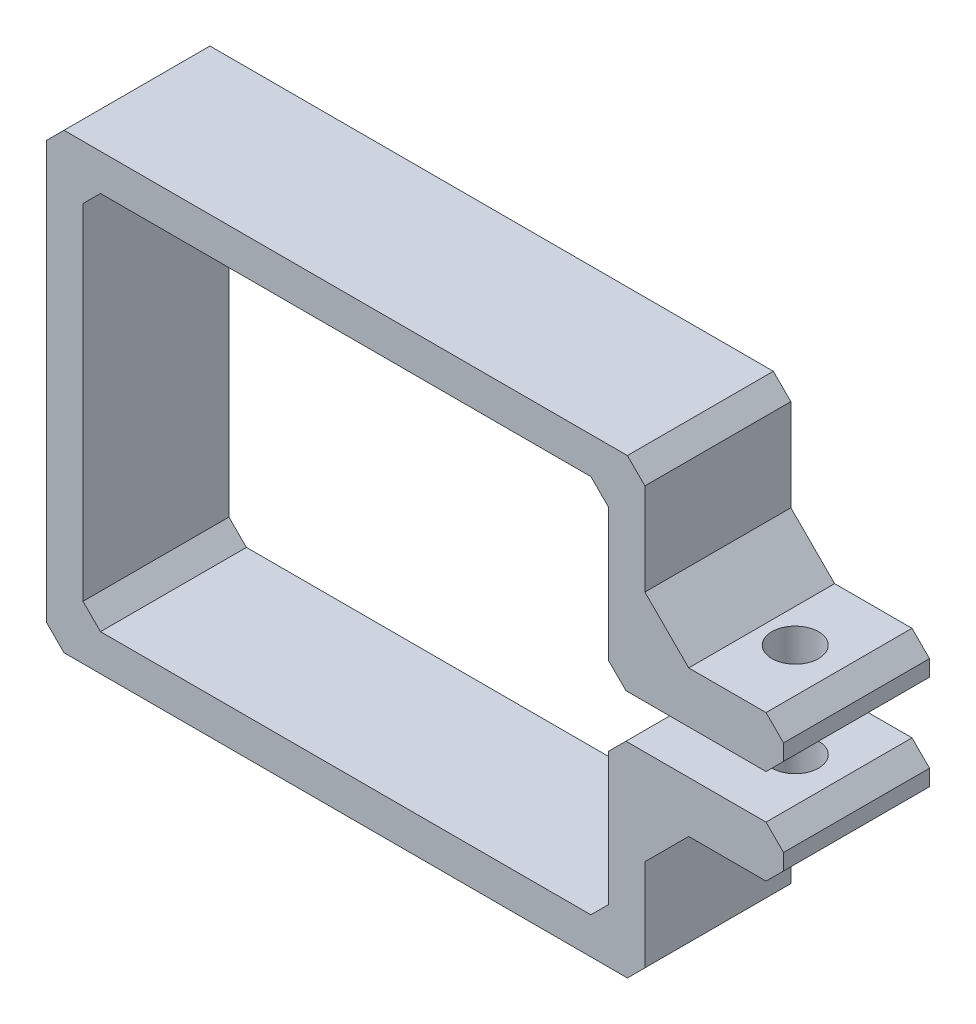
SolidWorks part; units mm, degrees
ref_plane "Front Plane" through (0, 0, 0) normal (0, 0, 1) x (1, 0, 0)
ref_plane "Top Plane" through (0, 0, 0) normal (0, 1, 0) x (1, 0, 0)
ref_plane "Right Plane" through (0, 0, 0) normal (1, 0, 0) x (0, 0, -1)
sketch "Sketch1" plane through (0, 0, 0) normal (0, 0, 1) x (1, 0, 0)
  line L0 (-20.5, 15.5) -> (-20.5, -15.5)
  line L1 (-18, 13) -> (18, 13)
  line L2 (-18, 13) -> (-18, -13)
  line L3 (-18, -13) -> (18, -13)
  line L4 (18, 13) -> (18, -13)
  line L5 (-18, 13) -> (18, -13) construction
  line L6 (-18, -13) -> (18, 13) construction
  line L7 (-20.5, -15.5) -> (20.5, -15.5)
  line L8 (20.5, 15.5) -> (20.5, -15.5)
  line L9 (-20.5, 15.5) -> (20.5, 15.5)
  line L11 (18, 5) -> (30, 5)
  line L12 (18, 5) -> (18, -5)
  line L13 (18, -5) -> (30, -5)
  line L14 (30, 5) -> (30, -5)
  line L15 (18, 5) -> (30, -5) construction
  line L16 (18, -5) -> (30, 5) construction
  line L17 (18, 1.5) -> (30, 1.5)
  line L18 (18, 1.5) -> (18, -1.5)
  line L19 (18, -1.5) -> (30, -1.5)
  line L20 (30, 1.5) -> (30, -1.5)
  line L21 (18, 1.5) -> (30, -1.5) construction
  line L22 (18, -1.5) -> (30, 1.5) construction
  point P0 (0, 0)
  point P14 (24, 0)
  point P19 (24, 0)
  point P20 (0, 0)
  point P21 (0, 0)
  dimension "D1" = 36
  dimension "D2" = 26
  dimension "D3" = 2.5
  dimension "D4" = 10
  dimension "D5" = 12
  dimension "D6" = 3
extrude "Boss-Extrude1" add sketch "Sketch1" along normal blind 10 contours L8 L17 L14 L11 | L13 L4 L3 L2 L1 L11 L8 L9 L0 L7 | L19 L4 L13 L8 | L4 L17 L8 L11 | L19 L8 L13 L14
chamfer "Chamfer1" distance 3 angle 45 2 edges at (20.5, -5, 5) (20.5, 5, 5)
chamfer "Chamfer2" distance 1.2 angle 45 14 edges at (30, 5, 5) (30, 1.5, 5) (18, 1.5, 5) (18, 13, 5) (-18, 13, 5) (-18, -13, 5) (18, -13, 5) (18, -1.5, 5) (30, -1.5, 5) (30, -5, 5) (20.5, -15.5, 5) (-20.5, -15.5, 5) (-20.5, 15.5, 5) (20.5, 15.5, 5)
sketch "Sketch2" plane through (0, 5, 0) normal (0, 1, 0) x (1, 0, 0)
  line L0 (28.8, -10) -> (28.8, 0) construction
  circle A0 centre (25.8, -5) radius 1.6
  point P4 (28.8, -5)
  dimension "D1" = 3.2
  dimension "D2" = 3
extrude "Cut-Extrude1" cut sketch "Sketch2" against normal blind 10
